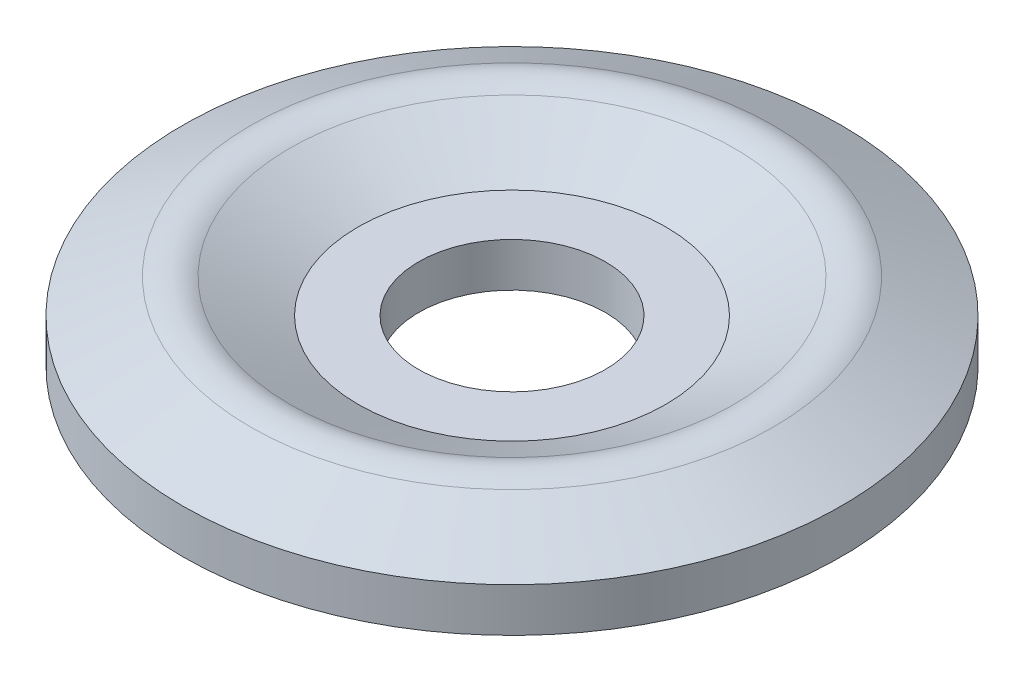
SolidWorks part; units mm, degrees
ref_plane "Front Plane" through (0, 0, 0) normal (0, 0, 1) x (1, 0, 0)
ref_plane "Top Plane" through (0, 0, 0) normal (0, 1, 0) x (1, 0, 0)
ref_plane "Right Plane" through (0, 0, 0) normal (1, 0, 0) x (0, 0, -1)
sketch "Sketch1" plane through (0, 0, 0) normal (1, 0, 0) x (0, 0, -1)
  line L0 (-15, -2) -> (-11, 0)
  line L1 (-15, -2) -> (15, -2)
  line L2 (-15, -2) -> (-15, 2)
  line L3 (-15, 2) -> (15, 2)
  line L4 (15, -2) -> (15, 2)
  line L5 (-15, -2) -> (15, 2) construction
  line L6 (-15, 2) -> (15, -2) construction
  line L7 (-11, 0) -> (-7, -2)
  line L8 (-11, 0) -> (-11, 2) construction
  line L9 (0, -2) -> (0, 2)
  line L10 (11, 0) -> (7, -2)
  line L11 (15, -2) -> (11, 0)
  line L12 (11, 0) -> (11, 2) construction
  line L13 (-11, 2) -> (-15, 0)
  line L14 (-11, 2) -> (-7, 0)
  line L15 (-7, 0) -> (-4.25, 0)
  line L16 (-4.25, 0) -> (-4.25, -2)
  line L17 (4.25, 0) -> (4.25, -2)
  line L18 (7, 0) -> (4.25, 0)
  line L19 (11, 2) -> (15, 0)
  line L20 (11, 2) -> (7, 0)
  point P0 (0, 0)
  dimension "D1" = 4
  dimension "D2" = 30
  dimension "D3" = 2
  dimension "D4" = 22
  dimension "D5" = 8
  dimension "D6" = 2
  dimension "D7" = 8.5
revolve "Revolve1" add sketch "Sketch1" angle 360 about L9
fillet "Fillet1" radius 2 2 edges at (0, 2, -11) (0, 0, -11)
